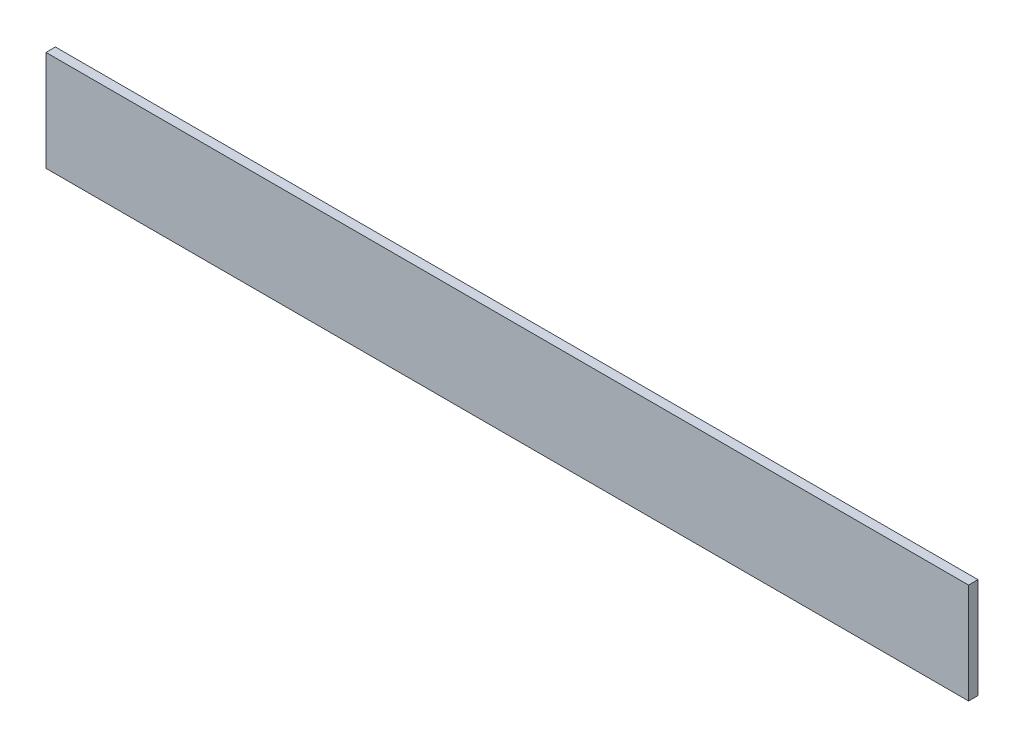
SolidWorks part; units mm, degrees
ref_plane "前视基准面" through (0, 0, 0) normal (0, 0, 1) x (1, 0, 0)
ref_plane "上视基准面" through (0, 0, 0) normal (0, 1, 0) x (1, 0, 0)
ref_plane "右视基准面" through (0, 0, 0) normal (1, 0, 0) x (0, 0, -1)
sketch "草图1" plane through (0, 0, 0) normal (0, 0, 1) x (1, 0, 0)
  line L1 (-147, 16) -> (147, 16)
  line L2 (-147, 16) -> (-147, -16)
  line L3 (-147, -16) -> (147, -16)
  line L4 (147, 16) -> (147, -16)
  line L5 (-147, 16) -> (147, -16) construction
  line L6 (-147, -16) -> (147, 16) construction
  point P0 (0, 0)
  dimension "D1" = 294
  dimension "D2" = 32
extrude "凸台-拉伸1" add sketch "草图1" along normal mid plane 3
